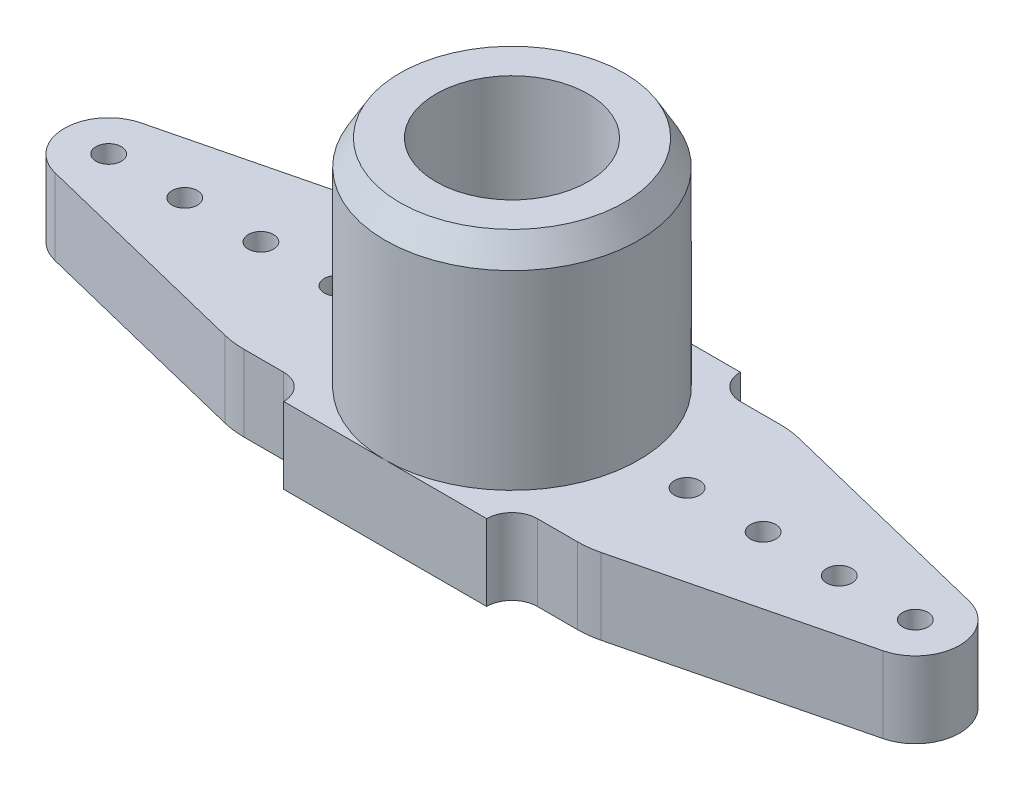
SolidWorks part; units mm, degrees
ref_plane "Alzado" through (0, 0, 0) normal (0, 0, 1) x (1, 0, 0)
ref_plane "Planta" through (0, 0, 0) normal (0, 1, 0) x (1, 0, 0)
ref_plane "Vista lateral" through (0, 0, 0) normal (1, 0, 0) x (0, 0, -1)
sketch "Croquis1" plane through (0, 0, 0) normal (0, 1, 0) x (1, 0, 0)
  line L0 (-4, 0) -> (-4, 6.5743)
  line L1 (-3.898, 7.4133) -> (-1.699, 16.3191)
  line L2 (1.699, 16.3191) -> (3.898, 7.4133)
  line L3 (4, 6.5743) -> (4, 0)
  line L4 (4, 0) -> (1.25, 0)
  line L5 (-4, 0) -> (-1.25, 0)
  line L6 (0, 0) -> (0, 23.2) construction
  arc A0 (1.25, 0) -> (-1.25, 0) centre (0, 0) ccw
  arc A1 (-1.699, 16.3191) -> (1.699, 16.3191) centre (0, 15.8996) cw
  arc A2 (-4, 6.5743) -> (-3.898, 7.4133) centre (-0.5, 6.5743) cw
  arc A3 (3.898, 7.4133) -> (4, 6.5743) centre (0.5, 6.5743) cw
  circle A4 centre (0, 15.8996) radius 0.5
  circle A5 centre (0, 12.8996) radius 0.5
  circle A6 centre (0, 9.8996) radius 0.5
  circle A7 centre (0, 6.8996) radius 0.5
  point P14 (-4, 7)
  dimension "D1" = 1.25
  dimension "D5" = 1.75
  dimension "D6" = 3.5
  dimension "D7" = 1
  dimension "D9" = 1
  dimension "D2" = 8
  dimension "D3" = 7
  dimension "D4" = 23.2
  dimension "D8" = 4
extrude "Saliente-Extruir1" add sketch "Croquis1" along normal blind 3
pattern_circular "MatrizC1" count 4 every 90 about axis through (0, 0, 0) along (0, 1, 0) of "Saliente-Extruir1"
sketch "Croquis2" plane through (0, 3, 0) normal (0, 1, 0) x (1, 0, 0)
  circle A0 centre (0, 0) radius 3
  circle A1 centre (0, 0) radius 5
  dimension "D1" = 6
  dimension "D2" = 10
extrude "Saliente-Extruir2" add sketch "Croquis2" along normal blind 8.5
chamfer "Chaflán1" distance 1 angle 30 1 edges at (0, 11.5, 5)
fillet "Redondeo1" radius 1 4 edges at (4, 1.5, -4) (-4, 1.5, -4) (-4, 1.5, 4) (4, 1.5, 4)
sketch "Croquis5" plane through (0, 0, 0) normal (0, 1, 0) x (1, 0, 0)
  line L16 (6.5743, 4) -> (5, 4)
  line L17 (4, 5) -> (4, 6.5743)
  line L18 (3.898, 7.4133) -> (1.699, 16.3191)
  line L19 (-1.699, 16.3191) -> (-3.898, 7.4133)
  line L20 (-4, 6.5743) -> (-4, 5)
  line L21 (-5, 4) -> (-6.5743, 4)
  line L22 (-7.4133, 3.898) -> (-16.3191, 1.699)
  line L23 (-16.3191, -1.699) -> (-7.4133, -3.898)
  line L24 (-6.5743, -4) -> (-5, -4)
  line L25 (-4, -5) -> (-4, -6.5743)
  line L26 (-3.898, -7.4133) -> (-1.699, -16.3191)
  line L27 (1.699, -16.3191) -> (3.898, -7.4133)
  line L28 (4, -6.5743) -> (4, -5)
  line L29 (5, -4) -> (6.5743, -4)
  line L30 (7.4133, -3.898) -> (16.3191, -1.699)
  line L31 (16.3191, 1.699) -> (7.4133, 3.898)
  line L32 (6.5743, 4) -> (5, 4)
  line L33 (4, 5) -> (4, 6.5743)
  line L34 (3.898, 7.4133) -> (1.699, 16.3191)
  line L35 (-1.699, 16.3191) -> (-3.898, 7.4133)
  line L36 (-4, 6.5743) -> (-4, 5)
  line L37 (-5, 4) -> (-6.5743, 4)
  line L38 (-7.4133, 3.898) -> (-16.3191, 1.699)
  line L39 (-16.3191, -1.699) -> (-7.4133, -3.898)
  line L40 (-6.5743, -4) -> (-5, -4)
  line L41 (-4, -5) -> (-4, -6.5743)
  line L42 (-3.898, -7.4133) -> (-1.699, -16.3191)
  line L43 (1.699, -16.3191) -> (3.898, -7.4133)
  line L44 (4, -6.5743) -> (4, -5)
  line L45 (5, -4) -> (6.5743, -4)
  line L46 (7.4133, -3.898) -> (16.3191, -1.699)
  line L47 (16.3191, 1.699) -> (7.4133, 3.898)
  circle A0 centre (-9.8996, 0) radius 0.5 construction
  circle A1 centre (0, 9.8996) radius 0.5 construction
  circle A2 centre (9.8996, 0) radius 0.5 construction
  circle A3 centre (0, -6.8996) radius 0.5 construction
  circle A4 centre (-9.8996, 0) radius 0.5
  circle A5 centre (0, 9.8996) radius 0.5
  circle A6 centre (9.8996, 0) radius 0.5
  circle A7 centre (0, -6.8996) radius 0.5
  arc A16 (4, 5) -> (5, 4) centre (5, 5) ccw
  arc A17 (4, 6.5743) -> (3.898, 7.4133) centre (0.5, 6.5743) ccw
  arc A18 (1.699, 16.3191) -> (-1.699, 16.3191) centre (0, 15.8996) ccw
  arc A19 (-3.898, 7.4133) -> (-4, 6.5743) centre (-0.5, 6.5743) ccw
  arc A20 (-5, 4) -> (-4, 5) centre (-5, 5) ccw
  arc A21 (-6.5743, 4) -> (-7.4133, 3.898) centre (-6.5743, 0.5) ccw
  arc A22 (-16.3191, 1.699) -> (-16.3191, -1.699) centre (-15.8996, 0) ccw
  arc A23 (-7.4133, -3.898) -> (-6.5743, -4) centre (-6.5743, -0.5) ccw
  arc A24 (-4, -5) -> (-5, -4) centre (-5, -5) ccw
  arc A25 (-4, -6.5743) -> (-3.898, -7.4133) centre (-0.5, -6.5743) ccw
  arc A26 (-1.699, -16.3191) -> (1.699, -16.3191) centre (0, -15.8996) ccw
  arc A27 (3.898, -7.4133) -> (4, -6.5743) centre (0.5, -6.5743) ccw
  arc A28 (5, -4) -> (4, -5) centre (5, -5) ccw
  arc A29 (6.5743, -4) -> (7.4133, -3.898) centre (6.5743, -0.5) ccw
  arc A30 (16.3191, -1.699) -> (16.3191, 1.699) centre (15.8996, 0) ccw
  arc A31 (7.4133, 3.898) -> (6.5743, 4) centre (6.5743, 0.5) ccw
  arc A32 (4, 5) -> (5, 4) centre (5, 5) ccw
  arc A33 (4, 6.5743) -> (3.898, 7.4133) centre (0.5, 6.5743) ccw
  arc A34 (1.699, 16.3191) -> (-1.699, 16.3191) centre (0, 15.8996) ccw
  arc A35 (-3.898, 7.4133) -> (-4, 6.5743) centre (-0.5, 6.5743) ccw
  arc A36 (-5, 4) -> (-4, 5) centre (-5, 5) ccw
  arc A37 (-6.5743, 4) -> (-7.4133, 3.898) centre (-6.5743, 0.5) ccw
  arc A38 (-16.3191, 1.699) -> (-16.3191, -1.699) centre (-15.8996, 0) ccw
  arc A39 (-7.4133, -3.898) -> (-6.5743, -4) centre (-6.5743, -0.5) ccw
  arc A40 (-4, -5) -> (-5, -4) centre (-5, -5) ccw
  arc A41 (-4, -6.5743) -> (-3.898, -7.4133) centre (-0.5, -6.5743) ccw
  arc A42 (-1.699, -16.3191) -> (1.699, -16.3191) centre (0, -15.8996) ccw
  arc A43 (3.898, -7.4133) -> (4, -6.5743) centre (0.5, -6.5743) ccw
  arc A44 (5, -4) -> (4, -5) centre (5, -5) ccw
  arc A45 (6.5743, -4) -> (7.4133, -3.898) centre (6.5743, -0.5) ccw
  arc A46 (16.3191, -1.699) -> (16.3191, 1.699) centre (15.8996, 0) ccw
  arc A47 (7.4133, 3.898) -> (6.5743, 4) centre (6.5743, 0.5) ccw
  dimension "D1" = 0
sketch "Sketch1" plane through (0, 0, 0) normal (0, -1, 0) x (1, 0, 0)
  line L0 (4, 5) -> (-4, 5)
  line L1 (-4, 5) -> (-4, 20.8081)
  line L2 (-4, 20.8081) -> (5.4383, 20.8081)
  line L3 (5.4383, 20.8081) -> (5.4383, 5)
  line L4 (5.4383, 5) -> (4, 5)
  line L5 (17.6496, 0) -> (-17.6496, 0) construction
  line L6 (5.4383, -5) -> (4, -5)
  line L7 (4, -5) -> (-4, -5)
  line L8 (-4, -5) -> (-4, -20.8081)
  line L9 (5.4383, -20.8081) -> (5.4383, -5)
  line L10 (-4, -20.8081) -> (5.4383, -20.8081)
  arc A0 (16.3191, -1.699) -> (16.3191, 1.699) centre (15.8996, 0) ccw construction
  arc A1 (-16.3191, 1.699) -> (-16.3191, -1.699) centre (-15.8996, 0) ccw construction
extrude "Cut-Extrude1" cut sketch "Sketch1" against normal blind 10
